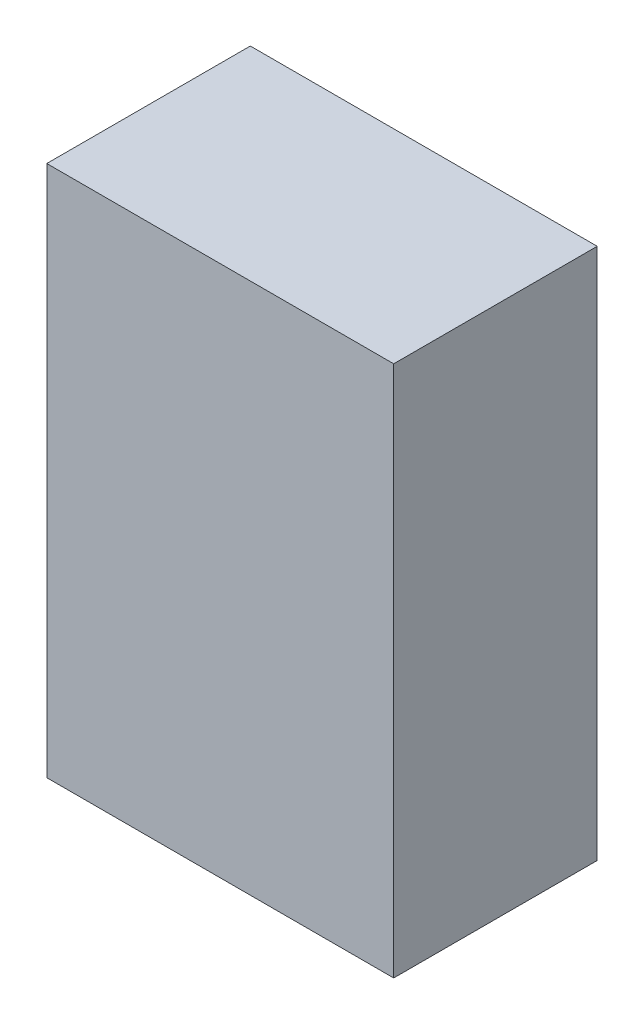
SolidWorks part; units mm, degrees
ref_plane "前视基准面" through (0, 0, 0) normal (0, 0, 1) x (1, 0, 0)
ref_plane "上视基准面" through (0, 0, 0) normal (0, 1, 0) x (1, 0, 0)
ref_plane "右视基准面" through (0, 0, 0) normal (1, 0, 0) x (0, 0, -1)
other "Configuration Table"
sketch "草图1" plane through (0, 0, 0) normal (0, 1, 0) x (1, 0, 0)
  line L1 (-15, 8.8) -> (15, 8.8)
  line L2 (-15, 8.8) -> (-15, -8.8)
  line L3 (-15, -8.8) -> (15, -8.8)
  line L4 (15, 8.8) -> (15, -8.8)
  line L5 (-15, 8.8) -> (15, -8.8) construction
  line L6 (-15, -8.8) -> (15, 8.8) construction
  point P0 (0, 0)
  dimension "D1" = 30
  dimension "D2" = 17.6
extrude "凸台-拉伸1" add sketch "草图1" along normal blind 46
